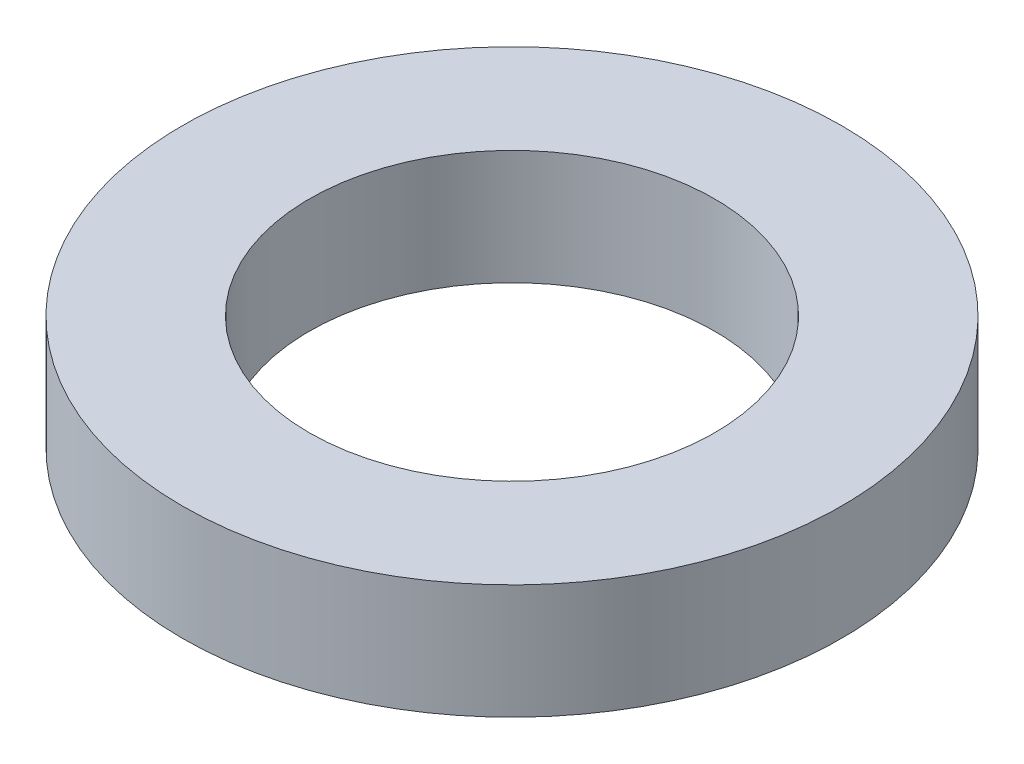
SolidWorks part; units mm, degrees
ref_plane "Front Plane" through (0, 0, 0) normal (0, 0, 1) x (1, 0, 0)
ref_plane "Top Plane" through (0, 0, 0) normal (0, 1, 0) x (1, 0, 0)
ref_plane "Right Plane" through (0, 0, 0) normal (1, 0, 0) x (0, 0, -1)
sketch "Sketch1" plane through (0, 0, 0) normal (0, 1, 0) x (1, 0, 0)
  circle A0 centre (0, 0) radius 2.0447
  dimension "OD" = 4.0894
extrude "Boss-Extrude1" add sketch "Sketch1" along normal blind 0.7112
sketch "Sketch5" plane through (0, 0.7112, 0) normal (0, 1, 0) x (-1, 0, 0)
  circle A0 centre (0, 0) radius 1.2573
  dimension "ID" = 2.5146
extrude "Cut-Extrude1" cut sketch "Sketch5" against normal through all
